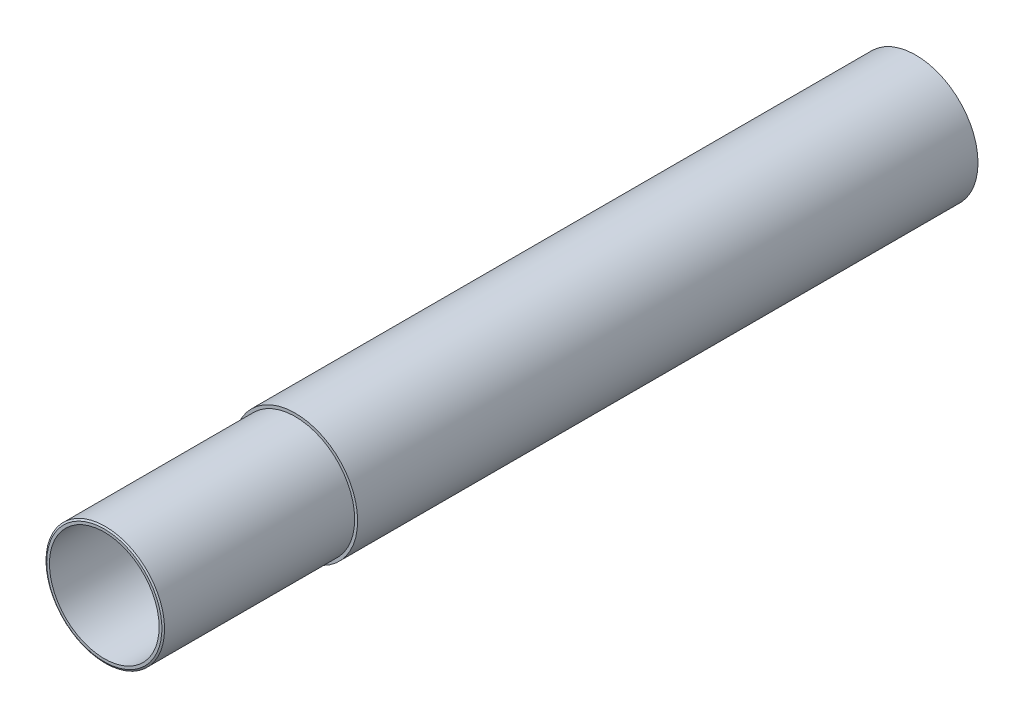
SolidWorks part; units mm, degrees
material "6061-T6 (SS)"
ref_plane "Front Plane" through (0, 0, 0) normal (0, 0, 1) x (1, 0, 0)
ref_plane "Top Plane" through (0, 0, 0) normal (0, 1, 0) x (1, 0, 0)
ref_plane "Right Plane" through (0, 0, 0) normal (1, 0, 0) x (0, 0, -1)
sketch "Sketch3" plane through (0, 0, 0) normal (0, 0, 1) x (1, 0, 0)
  line L0 (0, 29.3751) -> (0, 33.3375) construction
  circle A0 centre (0, 0) radius 29.3751
  circle A1 centre (0, 0) radius 33.3375
  dimension "D1" = 66.675
  dimension "D2" = 3.9624
extrude "Boss-Extrude1" add sketch "Sketch3" along normal mid plane 434.65
sketch "Sketch5" plane through (0, 0, 0) normal (1, 0, 0) x (0, 0, -1)
  line L0 (-217.325, 30.8375) -> (-215.8816, 33.3375)
  line L1 (-217.325, 33.3375) -> (-217.325, -33.3375) construction
  line L2 (217.325, 33.3375) -> (-217.325, 33.3375) construction
  line L3 (-215.8816, 33.3375) -> (-217.325, 33.3375)
  line L4 (-217.325, 33.3375) -> (-217.325, 30.8375)
  line L5 (0, 0) -> (-217.325, 0) construction
  dimension "D1" = 30
  dimension "D2" = 2.5
revolve "Cut-Revolve1" cut sketch "Sketch5" angle 360 about L5
sketch "Sketch4" plane through (0, 0, 217.325) normal (0, 0, 1) x (1, 0, 0)
  circle A0 centre (0, 0) radius 31.75
  circle A1 centre (0, 0) radius 33.3375 construction
  circle A2 centre (0, 0) radius 33.3375
  dimension "D1" = 63.5
extrude "Cut-Extrude1" cut sketch "Sketch4" against normal blind 102.35
